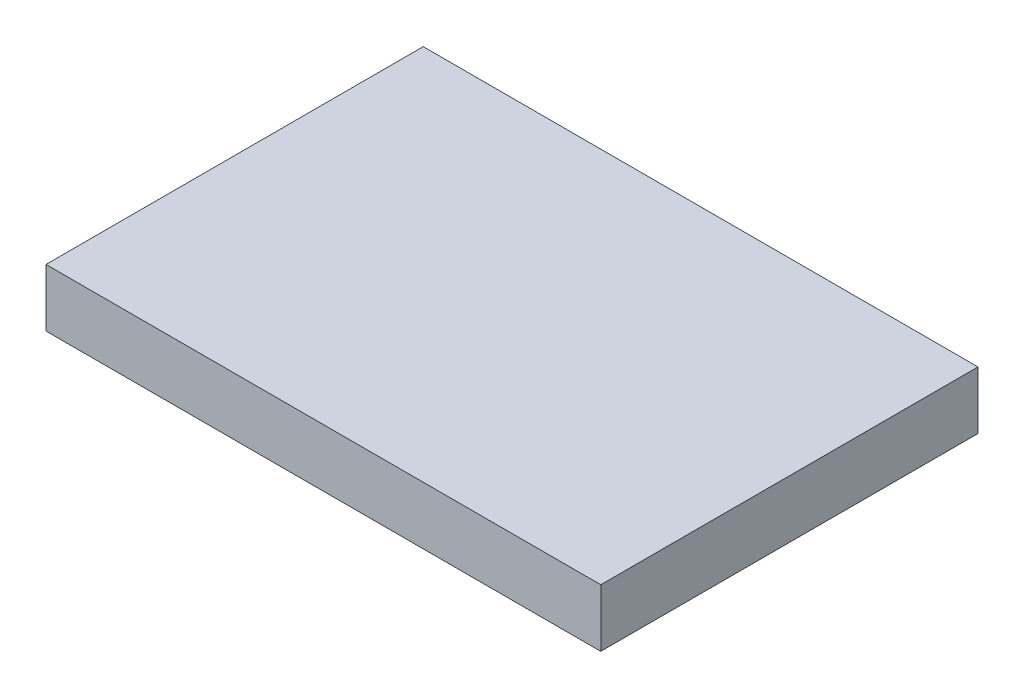
SolidWorks part; units mm, degrees
ref_plane "Front Plane" through (0, 0, 0) normal (0, 0, 1) x (1, 0, 0)
ref_plane "Top Plane" through (0, 0, 0) normal (0, 1, 0) x (1, 0, 0)
ref_plane "Right Plane" through (0, 0, 0) normal (1, 0, 0) x (0, 0, -1)
sketch "Sketch1" plane through (0, 0, 0) normal (0, 1, 0) x (1, 0, 0)
  line L1 (-25, -17) -> (25, -17)
  line L2 (-25, -17) -> (-25, 17)
  line L3 (-25, 17) -> (25, 17)
  line L4 (25, -17) -> (25, 17)
  line L5 (-25, -17) -> (25, 17) construction
  line L6 (-25, 17) -> (25, -17) construction
  point P0 (0, 0)
  dimension "D1" = 50
  dimension "D2" = 34
extrude "Boss-Extrude1" add sketch "Sketch1" along normal blind 5.2
